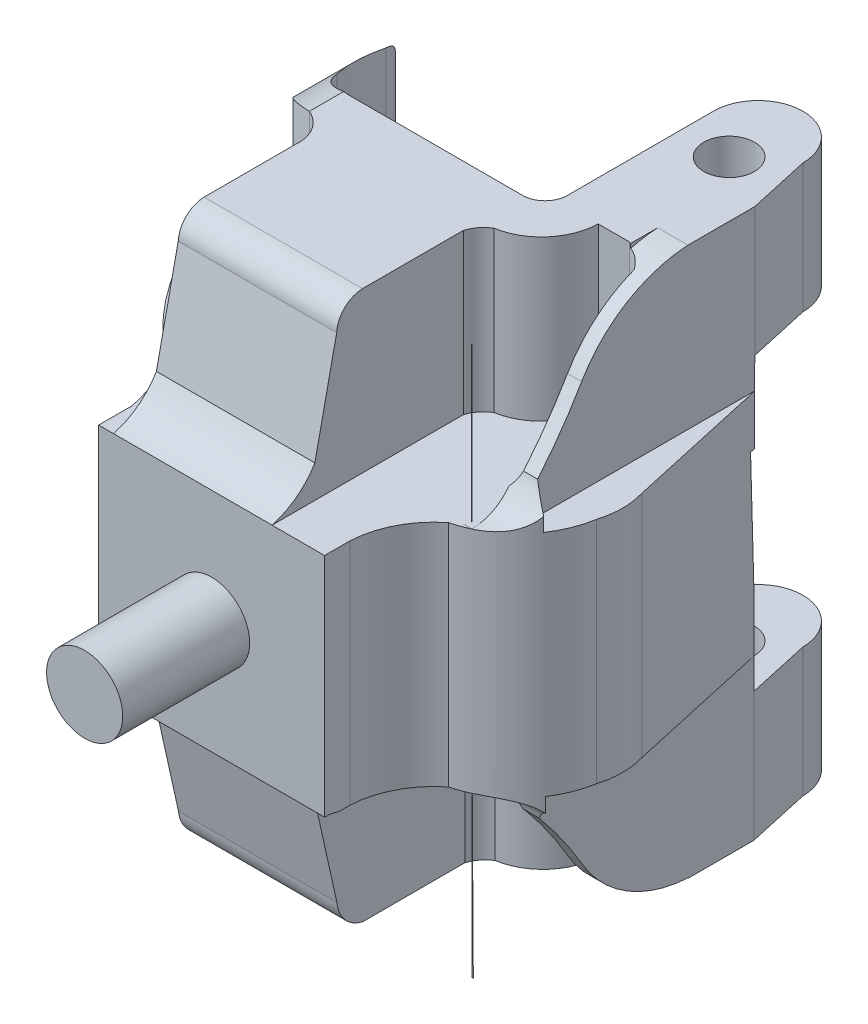
SolidWorks part; units mm, degrees
ref_plane "Front Plane" through (0, 0, 0) normal (0, 0, 1) x (1, 0, 0)
ref_plane "Top Plane" through (0, 0, 0) normal (0, 1, 0) x (1, 0, 0)
ref_plane "Right Plane" through (0, 0, 0) normal (1, 0, 0) x (0, 0, -1)
ref_plane "Plane1" through (0, 0, 0) normal (0, 1, 0) x (1, 0, 0)
sketch "Sketch2" plane through (0, 0, 0) normal (0, 1, 0) x (1, 0, 0)
  line L0 (0, 0) -> (-181.1731, 0) construction
  line L1 (0, 0) -> (181.1731, 0) construction
  line L2 (0, 0) -> (0, 174.625) construction
  line L3 (0, 174.625) -> (38.3822, 174.625) construction
  line L4 (38.3822, 174.625) -> (38.3822, 95.9485) construction
  line L5 (-79.2443, 0) -> (55.4409, 0)
  line L6 (74.468, 16.4026) -> (74.468, 72.8277)
  line L7 (0, 0) -> (0, -177.8046) construction
  line L8 (165.6666, 48.5518) -> (105.961, 48.5518) construction
  line L9 (181.1731, -30.2333) -> (145.0241, 132.5819)
  line L10 (-79.2443, -171.9521) -> (-79.2443, -544.4788)
  line L11 (-79.2443, -544.4788) -> (-88.2069, -544.4788)
  line L12 (-88.2069, -544.4788) -> (-88.2069, -578.3324)
  line L13 (-88.2069, -578.3324) -> (106.4078, -578.3324)
  line L14 (106.4078, -578.3324) -> (106.4078, -544.4788)
  line L15 (106.4078, -544.4788) -> (98.7308, -544.4788)
  line L16 (98.7308, -544.4788) -> (98.7308, -177.8046)
  line L17 (74.468, 72.8277) -> (74.468, 132.5819)
  line L18 (74.468, 132.5819) -> (145.0241, 132.5819) construction
  arc A0 (55.4409, 0) -> (74.468, 16.4026) centre (56.6714, 17.8097) ccw
  arc A5 (-79.2443, 0) -> (-113.1782, 23.6203) centre (-79.2443, 36.1856) cw
  arc A6 (98.7308, -177.8046) -> (125.1849, -126.6021) centre (168.2294, -181.2765) cw
  arc A7 (125.1849, -126.6021) -> (181.1731, -66.1354) centre (107.198, -53.7934) ccw
  arc A8 (181.1731, -66.1354) -> (181.1731, -30.2333) centre (121.7842, -48.1844) ccw
  arc A11 (-181.1731, 0) -> (-174.3141, 95.9485) centre (141.9049, 25.1237) cw
  arc A12 (-79.2443, -171.9521) -> (-104.3995, -120.9334) centre (-180.0191, -189.9291) ccw
  arc A13 (-104.3995, -120.9334) -> (-181.1731, 0) centre (47.1953, 60.1417) cw
  arc A14 (-113.1782, 23.6203) -> (-136.055, 85.4013) centre (155.9576, 158.4041) cw
  arc A15 (-136.055, 85.4013) -> (-163.9214, 106.7615) centre (-160.7266, 82.0721) ccw
  arc A16 (-174.3141, 95.9485) -> (-163.9214, 106.7615) centre (-160.803, 93.3634) cw
  arc A17 (74.468, 132.5819) -> (145.0241, 132.5819) centre (109.746, 132.5819) cw
extrude "Boss-Extrude1" add sketch "Sketch2" along normal blind 431.8
ref_plane "Plane2" through (0, 0, 0) normal (1, 0, 0) x (0, 0, -1)
sketch "Sketch3" plane through (0, 0, 0) normal (1, 0, 0) x (0, 0, -1)
  line L0 (-578.3324, 215.9) -> (-544.4788, 215.9) construction
  line L2 (-578.3324, 431.8) -> (-578.3324, 0) construction
  line L3 (-544.4788, 431.8) -> (-544.4788, 0) construction
  line L4 (-544.4788, 215.9) -> (-177.8046, 215.9) construction
  line L5 (-177.8046, 431.8) -> (-177.8046, 0) construction
  line L6 (-177.8046, 215.9) -> (-126.6021, 215.9) construction
  line L7 (-126.6021, 431.8) -> (-126.6021, 0) construction
  line L8 (-177.8046, 215.9) -> (-177.8046, 304.8) construction
  line L9 (-177.8046, 215.9) -> (-177.8046, 127) construction
  line L10 (-204.2811, 127) -> (-544.4788, 127)
  line L11 (-544.4788, 127) -> (-544.4788, 100.5284)
  line L12 (-544.4788, 431.8) -> (-544.4788, 0) construction
  line L13 (-544.4788, 100.5284) -> (-578.3324, 100.5284)
  line L14 (-578.3324, 100.5284) -> (-578.3324, 0)
  line L15 (-578.3324, 0) -> (-126.6021, 0)
  line L16 (-204.2811, 304.8) -> (-544.4788, 304.8)
  line L17 (-544.4788, 304.8) -> (-544.4788, 331.6689)
  line L18 (-544.4788, 331.6689) -> (-578.3324, 331.6689)
  line L19 (-578.3324, 331.6689) -> (-578.3324, 431.8)
  line L20 (-578.3324, 431.8) -> (-126.6021, 431.8)
  line L21 (-164.1658, 331.6689) -> (-146.9735, 411.8995)
  line L22 (-164.1658, 100.5284) -> (-146.9735, 23.1243)
  arc A0 (-204.2811, 127) -> (-164.1658, 100.5284) centre (-197.9023, 93.0352) cw
  arc A1 (-204.2811, 304.8) -> (-164.1658, 331.6689) centre (-212.5305, 360.4969) ccw
  arc A2 (-146.9735, 23.1243) -> (-126.6021, 0) centre (-120.9886, 25.4805) ccw
  arc A3 (-146.9735, 411.8995) -> (-126.6021, 431.8) centre (-126.0304, 410.8378) cw
extrude "Cut-Extrude1" cut sketch "Sketch3" against normal blind 190.5 and the other way blind 190.5
ref_plane "Plane3" through (0, 431.8, 0) normal (0, 1, 0) x (1, 0, 0)
sketch "Sketch4" plane through (0, 431.8, 0) normal (0, 1, 0) x (1, 0, 0)
  line L0 (155.8456, -87.211) -> (155.8456, 83.8419)
  line L1 (57.3181, -164.1658) -> (57.3181, -47.1303)
  line L2 (181.1731, -30.2333) -> (145.0241, 132.5819) construction
  line L3 (155.8456, -87.211) -> (177.8769, -101.3741)
  line L4 (177.8769, -101.3741) -> (226.395, -1.6845)
  line L5 (226.395, -1.6845) -> (155.8456, 83.8419)
  line L6 (144.698, -87.211) -> (144.698, 0)
  line L7 (130.535, 10.3565) -> (106.0505, 10.3565)
  line L9 (100.7806, -164.1658) -> (-80.9485, -164.1658) construction
  line L10 (144.698, -87.211) -> (138.6162, -92.6873)
  line L11 (138.6162, -92.6873) -> (138.6162, -164.1658)
  line L13 (-174.3141, 95.9485) -> (-160.803, 93.3634)
  line L14 (-67.5016, -54.3052) -> (-67.5016, -164.1658)
  line L16 (-106.0749, -164.1658) -> (-212.544, 0)
  line L17 (-212.544, 0) -> (-212.544, 95.9485)
  line L18 (-212.544, 95.9485) -> (-174.3141, 95.9485)
  line L19 (57.3181, -164.1658) -> (57.3181, -204.2811)
  line L20 (98.7308, -204.2811) -> (-79.2443, -204.2811) construction
  line L21 (57.3181, -204.2811) -> (138.6162, -204.2811)
  line L22 (138.6162, -204.2811) -> (138.6162, -164.1658)
  line L23 (-67.5016, -164.1658) -> (-67.5016, -204.2811)
  line L24 (-67.5016, -204.2811) -> (-94.8078, -204.2811)
  line L25 (-94.8078, -204.2811) -> (-106.0749, -164.1658)
  arc A0 (144.698, 0) -> (130.535, 10.3565) centre (124.7059, -12.4777) ccw
  arc A1 (-174.3141, 95.9485) -> (-181.1731, 0) centre (141.9049, 25.1237) ccw construction
  arc A2 (57.3181, -47.1303) -> (67.7738, -33.6872) centre (80.8109, -54.6149) cw
  arc A3 (67.7738, -33.6872) -> (106.0505, 10.3565) centre (60.1507, 11.592) ccw
  arc A4 (-163.9214, 106.7615) -> (-174.3141, 95.9485) centre (-160.803, 93.3634) ccw construction
  arc A5 (-160.803, 93.3634) -> (-146.9419, 64.7459) centre (-187.5705, 62.7327) cw
  arc A6 (-131.8856, 11.592) -> (-84.566, -26.667) centre (-57.7433, 54.9005) ccw
  arc A7 (-131.8856, 11.592) -> (-146.9419, 64.7459) centre (119.4804, 111.5026) cw
  arc A8 (-84.566, -26.667) -> (-67.5016, -54.3052) centre (-94.8078, -52.0775) cw
extrude "Cut-Extrude2" cut sketch "Sketch4" against normal blind 125.73
ref_plane "Plane4" through (0, 0, 0) normal (0, 0, 1) x (1, 0, 0)
sketch "Sketch6" plane through (0, 0, 0) normal (0, 0, 1) x (1, 0, 0)
  line L0 (-146.9419, 306.07) -> (-146.9419, 431.8) construction
  line L1 (-160.803, 306.07) -> (-160.803, 431.8) construction
  line L2 (-181.1731, 306.07) -> (-200.2867, 306.07)
  line L3 (-200.2867, 306.07) -> (-200.2867, 431.8)
  line L4 (201.2864, 431.8) -> (-201.2864, 431.8) construction
  line L5 (-200.2867, 431.8) -> (-84.566, 431.8)
  line L6 (-88.2069, 216.0987) -> (106.4078, 216.0987) construction
  line L7 (-88.2069, 331.6689) -> (-88.2069, 100.5284) construction
  line L8 (106.4078, 331.6689) -> (106.4078, 100.5284) construction
  line L9 (-181.1731, 126.1273) -> (-200.2867, 126.1273)
  line L11 (-200.2867, 126.1273) -> (-200.2867, 0.3973)
  line L12 (-200.2867, 0.3973) -> (-200.2867, -9.3355)
  line L13 (-200.2867, -9.3355) -> (-84.566, -9.3355)
  line L14 (-84.566, -9.3355) -> (-84.566, 0.3973)
  arc A0 (-84.566, 431.8) -> (-146.9419, 368.935) centre (-59.7662, 344.8155) ccw
  arc A1 (-181.1731, 306.07) -> (-160.803, 334.9279) centre (-210.7247, 348.5482) ccw
  arc A2 (-160.803, 334.9279) -> (-146.9419, 368.935) centre (-222.3693, 379.8504) ccw
  arc A3 (-181.1731, 126.1273) -> (-160.803, 97.2695) centre (-210.7247, 83.6492) cw
  arc A4 (-160.803, 97.2695) -> (-146.9419, 63.2623) centre (-222.3693, 52.3469) cw
  arc A5 (-84.566, 0.3973) -> (-146.9419, 63.2623) centre (-59.7662, 87.3819) cw
extrude "Cut-Extrude4" cut sketch "Sketch6" against normal blind 120.65 and the other way blind 128.27
sketch "Sketch7" plane through (0, 0, 0) normal (0, 1, 0) x (1, 0, 0)
  line L0 (156.0495, -86.3089) -> (156.0495, 84.7441)
  line L1 (57.522, -163.2636) -> (57.522, -46.2281)
  line L2 (156.0495, -86.3089) -> (178.0809, -100.4719)
  line L3 (178.0809, -100.4719) -> (226.5989, -0.7824)
  line L4 (226.5989, -0.7824) -> (156.0495, 84.7441)
  line L5 (144.9019, -86.3089) -> (144.9019, 0.9022)
  line L6 (130.7389, 11.2586) -> (106.2545, 11.2586)
  line L7 (144.9019, -86.3089) -> (138.8201, -91.7852)
  line L8 (138.8201, -91.7852) -> (138.8201, -163.2636)
  line L9 (-174.1102, 96.8507) -> (-160.5991, 94.2656)
  line L10 (-67.2977, -53.403) -> (-67.2977, -163.2636)
  line L11 (-105.871, -163.2636) -> (-212.3401, 0.9022)
  line L12 (-212.3401, 0.9022) -> (-212.3401, 96.8507)
  line L13 (-212.3401, 96.8507) -> (-174.1102, 96.8507)
  line L14 (57.522, -163.2636) -> (57.522, -203.3789)
  line L15 (57.522, -203.3789) -> (138.8201, -203.3789)
  line L16 (138.8201, -203.3789) -> (138.8201, -163.2636)
  line L17 (-67.2977, -163.2636) -> (-67.2977, -203.3789)
  line L18 (-67.2977, -203.3789) -> (-94.6039, -203.3789)
  line L19 (-94.6039, -203.3789) -> (-105.871, -163.2636)
  arc A0 (144.9019, 0.9022) -> (130.7389, 11.2586) centre (124.9098, -11.5755) ccw
  arc A1 (57.522, -46.2281) -> (67.9777, -32.7851) centre (81.0149, -53.7127) cw
  arc A2 (67.9777, -32.7851) -> (106.2545, 11.2586) centre (60.3547, 12.4942) ccw
  arc A3 (-160.5991, 94.2656) -> (-146.7379, 65.6481) centre (-187.3665, 63.6349) cw
  arc A4 (-131.6817, 12.4942) -> (-84.3621, -25.7648) centre (-57.5394, 55.8026) ccw
  arc A5 (-131.6817, 12.4942) -> (-146.7379, 65.6481) centre (119.6844, 112.4048) cw
  arc A6 (-84.3621, -25.7648) -> (-67.2977, -53.403) centre (-94.6039, -51.1753) cw
extrude "Cut-Extrude5" cut sketch "Sketch7" along normal blind 125.73
sketch "Sketch8" plane through (0, 0, 0) normal (1, 0, 0) x (0, 0, -1)
  line L0 (167.8599, 215.9) -> (167.8599, 330.2) construction
  line L1 (167.8599, 0) -> (167.8599, 431.8) construction
  line L2 (167.8599, 215.9) -> (167.8599, 101.6)
  line L3 (167.8599, 101.6) -> (82.9234, 101.6)
  line L4 (82.9234, 0) -> (82.9234, 125.73) construction
  line L5 (82.9234, 101.6) -> (83.8419, 330.2)
  line L6 (83.8419, 306.07) -> (83.8419, 431.8) construction
  line L7 (83.8419, 330.2) -> (167.8599, 330.2)
  line L8 (167.8599, 215.9) -> (167.8599, 330.2)
extrude "Cut-Extrude7" cut sketch "Sketch8" along normal blind 161.29
ref_plane "Plane5" through (177.8, 0, 0) normal (1, 0, 0) x (0, 0, -1)
sketch "Sketch9" plane through (177.8, 0, 0) normal (1, 0, 0) x (0, 0, -1)
  line L0 (-87.211, 306.07) -> (-87.211, 431.8) construction
  line L1 (201.2864, 431.8) -> (-201.2864, 431.8) construction
  line L2 (31.1301, 431.8) -> (31.1301, 493.4056)
  line L3 (31.1301, 493.4056) -> (-121.7481, 493.4056)
  line L4 (-121.7481, 493.4056) -> (-121.8928, 306.07)
  line L5 (106.9673, 216.0987) -> (-177.8046, 215.9) construction
  line L6 (106.9673, 97.1645) -> (106.9673, 335.0328) construction
  line L7 (-177.8046, 306.07) -> (-177.8046, 125.73) construction
  line L8 (-121.3609, -61.5271) -> (-121.7671, 125.8081)
  line L9 (31.517, -61.3138) -> (-121.3609, -61.5271)
  line L10 (31.4311, 0.2917) -> (31.517, -61.3138)
  arc A0 (-121.8928, 306.07) -> (-87.211, 331.3299) centre (-121.7481, 342.3102) ccw
  arc A1 (31.1301, 431.8) -> (-52.5498, 380.5393) centre (36.8707, 328.4973) ccw
  arc A2 (-87.211, 331.3299) -> (-52.5498, 380.5393) centre (-353.3735, 555.6165) ccw
  arc A3 (31.4311, 0.2917) -> (-52.3202, 51.4356) centre (37.0276, 103.6023) cw
  arc A4 (-87.0501, 100.5966) -> (-52.3202, 51.4356) centre (-352.8994, -124.0611) cw
  arc A5 (-121.7671, 125.8081) -> (-87.0501, 100.5966) centre (-121.5717, 89.5681) cw
extrude "Cut-Extrude8" cut sketch "Sketch9" against normal blind 45.72
sketch "Sketch10" plane through (0, 0, 0) normal (1, 0, 0) x (0, 0, -1)
  line L0 (-544.4788, 216.0987) -> (-177.8046, 215.9) construction
  line L1 (-544.4788, 331.6689) -> (-544.4788, 100.5284) construction
  line L2 (-177.8046, 306.07) -> (-177.8046, 125.73) construction
  line L3 (-514.3219, 216.0823) -> (-514.3219, 237.6695) construction
  line L4 (-514.3219, 237.6695) -> (-471.6464, 237.6695) construction
  line L5 (-471.6464, 237.6695) -> (-471.6464, 216.0592) construction
  line L6 (-428.9708, 216.0361) -> (-514.3219, 216.0823) construction
  line L7 (-428.9832, 193.2296) -> (-514.3342, 193.2758)
  line L8 (-428.9585, 238.8426) -> (-514.3095, 238.8888)
  arc A0 (-428.9832, 193.2296) -> (-428.9585, 238.8426) centre (-428.9708, 216.0361) ccw
  arc A1 (-514.3095, 238.8888) -> (-514.3342, 193.2758) centre (-514.3219, 216.0823) ccw
  point P11 (-471.6464, 216.0592)
extrude "Cut-Extrude9" cut sketch "Sketch10" against normal blind 88.9 and the other way blind 104.14
sketch "Sketch12" plane through (0, 0, 0) normal (0, 1, 0) x (1, 0, 0)
  circle A1 centre (111.8124, 107.6562) radius 20
extrude "Cut-Extrude10" cut sketch "Sketch12" along normal blind 431.8
sketch "Sketch13" plane through (0, 0, 0) normal (0, 0, 1) x (1, 0, 0)
  line L0 (197.3307, 215.9633) -> (197.3307, 266.7633) construction
  line L1 (197.3307, 215.9633) -> (197.3307, 165.1633) construction
  line L2 (156.7935, 266.7633) -> (-63.9981, 266.7633)
  line L3 (155.9928, 165.1633) -> (-63.9981, 165.1633)
  line L5 (197.3307, 215.9633) -> (-113.1782, 216.0987) construction
  line L6 (-113.1782, 417.8121) -> (-113.1782, 14.3853) construction
  line L7 (156.7935, 266.7633) -> (155.9928, 165.1633)
  line L8 (155.8671, 306.07) -> (156.0495, 101.6) construction
  arc A0 (-63.9981, 266.7633) -> (-63.9981, 165.1633) centre (-62.6772, 215.9633) ccw
extrude "Cut-Extrude11" cut sketch "Sketch13" against normal blind 88.9 and the other way blind 76.2
scale "Scale1" bodies to scale 110 113 scale about origin uniform scaling yes scale factor 0.1
sketch "Sketch15" plane through (0, 0, 57.8332) normal (0, 0, 1) x (1, 0, 0)
  line L1 (10.6408, 10.0528) -> (-8.8207, 10.0528)
  line L2 (10.6408, 10.0528) -> (10.6408, 33.1669)
  line L3 (10.6408, 33.1669) -> (-8.8207, 33.1669)
  line L4 (-8.8207, 10.0528) -> (-8.8207, 33.1669)
extrude "Cut-Extrude12" cut sketch "Sketch15" against normal blind 38.04
sketch "Sketch16" plane through (0, 0, 19.7932) normal (0, 0, 1) x (1, 0, 0)
  line L0 (9.8731, 21.6832) -> (-7.9244, 21.6832) construction
  line L1 (9.8731, 12.7594) -> (9.8731, 30.607) construction
  line L2 (-7.9244, 30.607) -> (-7.9244, 12.7594) construction
  circle A0 centre (0.9743, 21.6832) radius 3
extrude "Boss-Extrude3" add sketch "Sketch16" along normal blind 10
